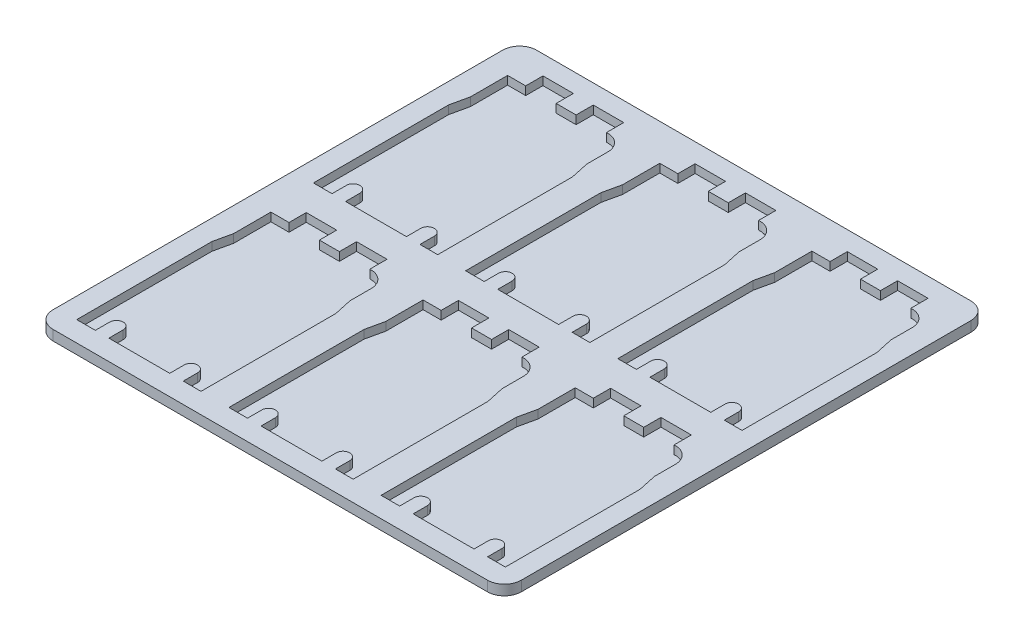
SolidWorks part; units mm, degrees
ref_plane "Front Plane" through (0, 0, 0) normal (0, 0, 1) x (1, 0, 0)
ref_plane "Top Plane" through (0, 0, 0) normal (0, 1, 0) x (1, 0, 0)
ref_plane "Right Plane" through (0, 0, 0) normal (1, 0, 0) x (0, 0, -1)
sketch "Sketch1" plane through (0, 0, 0) normal (0, 1, 0) x (1, 0, 0)
  line L1 (10, 0) -> (267, 0)
  line L2 (0, 10) -> (0, 276)
  line L3 (10, 286) -> (267, 286)
  line L4 (277, 10) -> (277, 276)
  arc A0 (267, 286) -> (277, 276) centre (267, 276) cw
  arc A1 (277, 10) -> (267, 0) centre (267, 10) cw
  arc A2 (10, 0) -> (0, 10) centre (10, 10) cw
  arc A3 (0, 276) -> (10, 286) centre (10, 276) cw
  point P11 (0, 0)
  dimension "D1" = 10
  dimension "D2" = 266
  dimension "D3" = 257
extrude "Boss-Extrude1" add sketch "Sketch1" along normal blind 6
sketch "Sketch2" plane through (0, 6, 0) normal (0, 1, 0) x (1, 0, 0)
  line L18 (0, 276) -> (0, 10) construction
  line L19 (10, 0) -> (267, 0) construction
  line L32 (12.0622, 92) -> (14.4027, 102.5)
  line L33 (83.2217, 102.5) -> (83.2217, 114.5)
  line L34 (85.5622, 91.74) -> (83.2217, 102.5)
  line L35 (85.5622, 12) -> (85.5622, 91.74)
  line L36 (85.5622, 12) -> (75.0622, 12)
  line L37 (75.0622, 12) -> (75.0622, 20.5)
  line L38 (67.0622, 12) -> (67.0622, 20.5)
  line L39 (67.0622, 12) -> (31.0622, 12)
  line L40 (31.0622, 12) -> (31.0622, 20.5)
  line L41 (23.0622, 12) -> (23.0622, 20.5)
  line L42 (23.0622, 12) -> (12.0622, 12)
  line L43 (12.0622, 12) -> (12.0622, 92)
  line L44 (14.4027, 102.5) -> (14.4027, 124.5)
  line L45 (25.1027, 124.5) -> (14.4027, 124.5)
  line L46 (25.1027, 124.5) -> (25.1027, 134.7)
  line L47 (43.1027, 134.7) -> (25.1027, 134.7)
  line L48 (43.1027, 124.5) -> (43.1027, 134.7)
  line L49 (54.9027, 124.5) -> (43.1027, 124.5)
  line L50 (54.9027, 124.5) -> (54.9027, 134.6635)
  line L51 (72.9027, 134.6635) -> (54.9027, 134.6635)
  line L52 (72.9027, 124.4635) -> (72.9027, 134.6635)
  line L53 (102.0622, 92) -> (104.4027, 102.5)
  line L54 (104.4027, 102.5) -> (104.4027, 124.5)
  line L55 (115.1027, 124.5) -> (104.4027, 124.5)
  line L56 (115.1027, 124.5) -> (115.1027, 134.7)
  line L57 (133.1027, 134.7) -> (115.1027, 134.7)
  line L58 (133.1027, 124.5) -> (133.1027, 134.7)
  line L59 (144.9027, 124.5) -> (133.1027, 124.5)
  line L60 (144.9027, 124.5) -> (144.9027, 134.6635)
  line L61 (162.9027, 134.6635) -> (144.9027, 134.6635)
  line L62 (162.9027, 124.4635) -> (162.9027, 134.6635)
  line L63 (173.2217, 102.5) -> (173.2217, 114.5)
  line L64 (175.5622, 91.74) -> (173.2217, 102.5)
  line L65 (175.5622, 12) -> (175.5622, 91.74)
  line L66 (175.5622, 12) -> (165.0622, 12)
  line L67 (165.0622, 12) -> (165.0622, 20.5)
  line L68 (157.0622, 12) -> (157.0622, 20.5)
  line L69 (157.0622, 12) -> (121.0622, 12)
  line L70 (121.0622, 12) -> (121.0622, 20.5)
  line L71 (113.0622, 12) -> (113.0622, 20.5)
  line L72 (113.0622, 12) -> (102.0622, 12)
  line L73 (102.0622, 12) -> (102.0622, 92)
  line L74 (192.0622, 92) -> (194.4027, 102.5)
  line L75 (194.4027, 102.5) -> (194.4027, 124.5)
  line L76 (205.1027, 124.5) -> (194.4027, 124.5)
  line L77 (205.1027, 124.5) -> (205.1027, 134.7)
  line L78 (223.1027, 134.7) -> (205.1027, 134.7)
  line L79 (223.1027, 124.5) -> (223.1027, 134.7)
  line L80 (234.9027, 124.5) -> (223.1027, 124.5)
  line L81 (234.9027, 124.5) -> (234.9027, 134.6635)
  line L82 (252.9027, 134.6635) -> (234.9027, 134.6635)
  line L83 (252.9027, 124.4635) -> (252.9027, 134.6635)
  line L84 (263.2217, 102.5) -> (263.2217, 114.5)
  line L85 (265.5622, 91.74) -> (263.2217, 102.5)
  line L86 (265.5622, 12) -> (265.5622, 91.74)
  line L87 (265.5622, 12) -> (255.0622, 12)
  line L88 (255.0622, 12) -> (255.0622, 20.5)
  line L89 (247.0622, 12) -> (247.0622, 20.5)
  line L90 (247.0622, 12) -> (211.0622, 12)
  line L91 (211.0622, 12) -> (211.0622, 20.5)
  line L92 (203.0622, 12) -> (203.0622, 20.5)
  line L93 (203.0622, 12) -> (192.0622, 12)
  line L94 (192.0622, 12) -> (192.0622, 92)
  line L95 (102.0622, 232) -> (104.4027, 242.5)
  line L96 (104.4027, 242.5) -> (104.4027, 264.5)
  line L97 (115.1027, 264.5) -> (104.4027, 264.5)
  line L98 (115.1027, 264.5) -> (115.1027, 274.7)
  line L99 (133.1027, 274.7) -> (115.1027, 274.7)
  line L100 (133.1027, 264.5) -> (133.1027, 274.7)
  line L101 (144.9027, 264.5) -> (133.1027, 264.5)
  line L102 (144.9027, 264.5) -> (144.9027, 274.6635)
  line L103 (162.9027, 274.6635) -> (144.9027, 274.6635)
  line L104 (162.9027, 264.4635) -> (162.9027, 274.6635)
  line L105 (173.2217, 242.5) -> (173.2217, 254.5)
  line L106 (175.5622, 231.74) -> (173.2217, 242.5)
  line L107 (175.5622, 152) -> (175.5622, 231.74)
  line L108 (175.5622, 152) -> (165.0622, 152)
  line L109 (165.0622, 152) -> (165.0622, 160.5)
  line L110 (157.0622, 152) -> (157.0622, 160.5)
  line L111 (157.0622, 152) -> (121.0622, 152)
  line L112 (121.0622, 152) -> (121.0622, 160.5)
  line L113 (113.0622, 152) -> (113.0622, 160.5)
  line L114 (113.0622, 152) -> (102.0622, 152)
  line L115 (102.0622, 152) -> (102.0622, 232)
  line L116 (192.0622, 232) -> (194.4027, 242.5)
  line L117 (194.4027, 242.5) -> (194.4027, 264.5)
  line L118 (205.1027, 264.5) -> (194.4027, 264.5)
  line L119 (205.1027, 264.5) -> (205.1027, 274.7)
  line L120 (223.1027, 274.7) -> (205.1027, 274.7)
  line L121 (223.1027, 264.5) -> (223.1027, 274.7)
  line L122 (234.9027, 264.5) -> (223.1027, 264.5)
  line L123 (234.9027, 264.5) -> (234.9027, 274.6635)
  line L124 (252.9027, 274.6635) -> (234.9027, 274.6635)
  line L125 (252.9027, 264.4635) -> (252.9027, 274.6635)
  line L126 (263.2217, 242.5) -> (263.2217, 254.5)
  line L127 (265.5622, 231.74) -> (263.2217, 242.5)
  line L128 (265.5622, 152) -> (265.5622, 231.74)
  line L129 (265.5622, 152) -> (255.0622, 152)
  line L130 (255.0622, 152) -> (255.0622, 160.5)
  line L131 (247.0622, 152) -> (247.0622, 160.5)
  line L132 (247.0622, 152) -> (211.0622, 152)
  line L133 (211.0622, 152) -> (211.0622, 160.5)
  line L134 (203.0622, 152) -> (203.0622, 160.5)
  line L135 (203.0622, 152) -> (192.0622, 152)
  line L136 (192.0622, 152) -> (192.0622, 232)
  line L137 (12.0622, 232) -> (14.4027, 242.5)
  line L138 (14.4027, 242.5) -> (14.4027, 264.5)
  line L139 (25.1027, 264.5) -> (14.4027, 264.5)
  line L140 (25.1027, 264.5) -> (25.1027, 274.7)
  line L141 (43.1027, 274.7) -> (25.1027, 274.7)
  line L142 (43.1027, 264.5) -> (43.1027, 274.7)
  line L143 (54.9027, 264.5) -> (43.1027, 264.5)
  line L144 (54.9027, 264.5) -> (54.9027, 274.6635)
  line L145 (72.9027, 274.6635) -> (54.9027, 274.6635)
  line L146 (72.9027, 264.4635) -> (72.9027, 274.6635)
  line L147 (83.2217, 242.5) -> (83.2217, 254.5)
  line L148 (85.5622, 231.74) -> (83.2217, 242.5)
  line L149 (85.5622, 152) -> (85.5622, 231.74)
  line L150 (85.5622, 152) -> (75.0622, 152)
  line L151 (75.0622, 152) -> (75.0622, 160.5)
  line L152 (67.0622, 152) -> (67.0622, 160.5)
  line L153 (67.0622, 152) -> (31.0622, 152)
  line L154 (31.0622, 152) -> (31.0622, 160.5)
  line L155 (23.0622, 152) -> (23.0622, 160.5)
  line L156 (23.0622, 152) -> (12.0622, 152)
  line L157 (12.0622, 152) -> (12.0622, 232)
  arc A5 (72.9027, 124.4635) -> (83.2217, 114.5) centre (73.7349, 115) cw
  arc A6 (75.0622, 20.5) -> (67.0622, 20.5) centre (71.0622, 20.5) ccw
  arc A7 (31.0622, 20.5) -> (23.0622, 20.5) centre (27.0622, 20.5) ccw
  arc A8 (162.9027, 124.4635) -> (173.2217, 114.5) centre (163.7349, 115) cw
  arc A9 (165.0622, 20.5) -> (157.0622, 20.5) centre (161.0622, 20.5) ccw
  arc A10 (121.0622, 20.5) -> (113.0622, 20.5) centre (117.0622, 20.5) ccw
  arc A11 (252.9027, 124.4635) -> (263.2217, 114.5) centre (253.7349, 115) cw
  arc A12 (255.0622, 20.5) -> (247.0622, 20.5) centre (251.0622, 20.5) ccw
  arc A13 (211.0622, 20.5) -> (203.0622, 20.5) centre (207.0622, 20.5) ccw
  arc A14 (162.9027, 264.4635) -> (173.2217, 254.5) centre (163.7349, 255) cw
  arc A15 (165.0622, 160.5) -> (157.0622, 160.5) centre (161.0622, 160.5) ccw
  arc A16 (121.0622, 160.5) -> (113.0622, 160.5) centre (117.0622, 160.5) ccw
  arc A17 (252.9027, 264.4635) -> (263.2217, 254.5) centre (253.7349, 255) cw
  arc A18 (255.0622, 160.5) -> (247.0622, 160.5) centre (251.0622, 160.5) ccw
  arc A19 (211.0622, 160.5) -> (203.0622, 160.5) centre (207.0622, 160.5) ccw
  arc A20 (72.9027, 264.4635) -> (83.2217, 254.5) centre (73.7349, 255) cw
  arc A21 (75.0622, 160.5) -> (67.0622, 160.5) centre (71.0622, 160.5) ccw
  arc A22 (31.0622, 160.5) -> (23.0622, 160.5) centre (27.0622, 160.5) ccw
  point P37 (189.7629, 97.25)
  dimension "D3" = 80
  dimension "D1" = 12.0622
  dimension "D2" = 12
  dimension "D4" = 10.76
  dimension "D5" = 3
extrude "Cut-Extrude1" cut sketch "Sketch2" against normal blind 5
